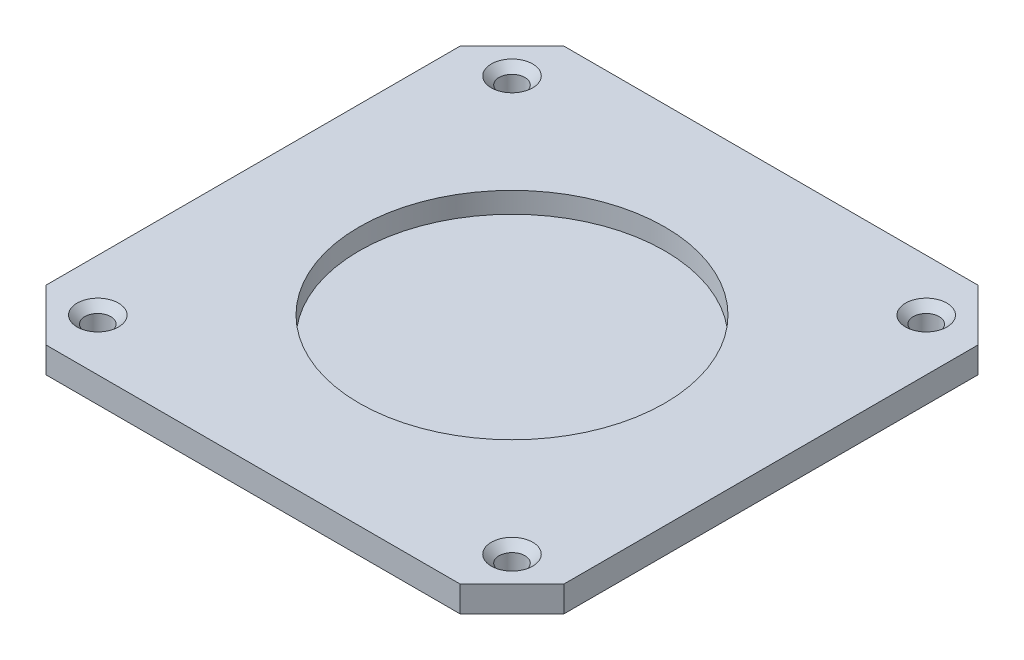
SolidWorks part; units mm, degrees
ref_plane "Front Plane" through (0, 0, 0) normal (0, 0, 1) x (1, 0, 0)
ref_plane "Top Plane" through (0, 0, 0) normal (0, 1, 0) x (1, 0, 0)
ref_plane "Right Plane" through (0, 0, 0) normal (1, 0, 0) x (0, 0, -1)
sketch "Sketch1" plane through (0, 0, 0) normal (0, 1, 0) x (1, 0, 0)
  line L1 (-50, -50) -> (50, -50)
  line L2 (-50, -50) -> (-50, 50)
  line L3 (-50, 50) -> (50, 50)
  line L4 (50, -50) -> (50, 50)
  line L5 (-50, -50) -> (50, 50) construction
  line L6 (-50, 50) -> (50, -50) construction
  point P0 (0, 0)
  dimension "D1" = 100
  dimension "D2" = 100
extrude "Boss-Extrude1" add sketch "Sketch1" along normal mid plane 5
hole_wizard "CSK for M5 Flat Head Machine Screw1" positions "Sketch2" profile "Sketch3" countersink size "M5" standard "ANSI Metric" end condition through all
sketch "Sketch2" plane through (0, 2.5, 0) normal (0, 1, 0) x (1, 0, 0)
  line L0 (-50, 50) -> (-50, -50) construction
  line L3 (50, 50) -> (-50, 50) construction
  point P0 (-40, 40)
  point P7 (-40.8887, 50)
  point P14 (-40.466, 50)
  dimension "D1" = 10
  dimension "D2" = 10
sketch "Sketch3" plane through (-40, 2.5, -40) normal (1, 0, 0) x (0, 0, 1)
  line L0 (0, 0) -> (0, 5)
  line L1 (0, 5) -> (2.5, 5)
  line L2 (2.5, 5) -> (2.5, 1.5)
  line L3 (2.5, 1.5) -> (4, 0)
  line L5 (4, 0) -> (0, 0)
  line L6 (-2.5, 1.5) -> (-4, 0) construction
  line L11 (0, -6.35) -> (0, 107.95) construction
  dimension "Thru Hole Dia." = 5
  dimension "Thru Hole Depth" = 5
  dimension "Near C'Sink Dia." = 8
  dimension "Near C'Sink Angle" = 90
chamfer "Chamfer1" distance 10 angle 45 4 edges at (-50, 0, -50) (-50, 0, 50) (50, 0, 50) (50, 0, -50)
hole_wizard "Ø1.0mm Clearance Dowel Hole1" positions "Sketch4" profile "Sketch5" hole size "Ø1.0" standard "ANSI Metric"
sketch "Sketch4" plane through (0, 2.5, 0) normal (0, 1, 0) x (1, 0, 0)
  point P0 (0, 0)
sketch "Sketch5" plane through (0, 2.5, 0) normal (1, 0, 0) x (0, 0, 1)
  line L0 (0, 0) -> (0, 4)
  line L1 (0, 4) -> (29.5, 4)
  line L2 (29.5, 4) -> (29.5, 0)
  line L5 (29.5, 0) -> (0, 0)
  line L10 (0, 4) -> (-29.5, 4) construction
  line L11 (0, -6.35) -> (0, 107.95) construction
  dimension "Hole Dia." = 59
  dimension "Hole Depth" = 4
  dimension "Drill Angle" = 180
pattern_circular "CirPattern3" count 4 over 360 about axis through (0, 0, 0) along (0, 1, 0) of "CSK for M5 Flat Head Machine Screw1"
